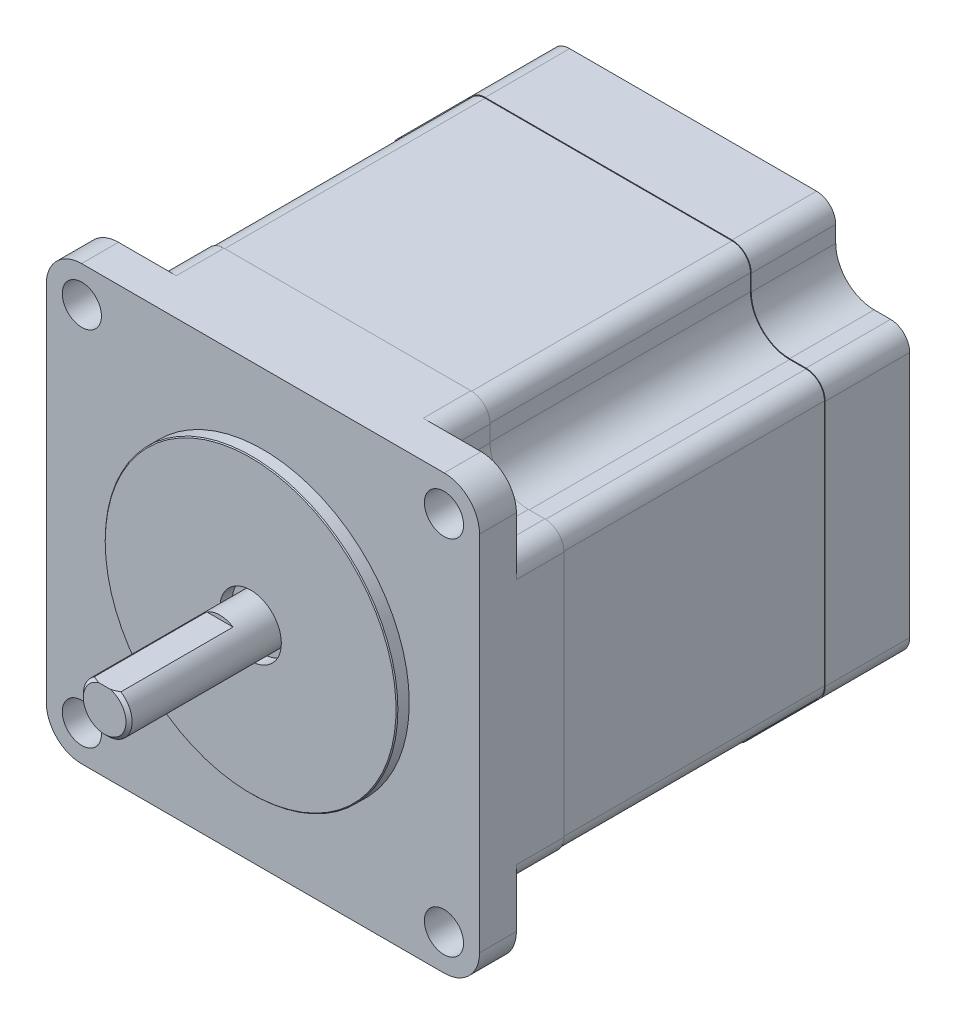
SolidWorks part; units mm, degrees
ref_plane "Front" through (0, 0, 0) normal (0, 0, 1) x (1, 0, 0)
ref_plane "Top" through (0, 0, 0) normal (0, 1, 0) x (1, 0, 0)
ref_plane "Right" through (0, 0, 0) normal (1, 0, 0) x (0, 0, -1)
sketch "Sketch1" plane through (0, 0, 0) normal (0, 0, 1) x (1, 0, 0)
  circle A0 centre (0, 0) radius 3.175
  dimension "D1" = 6.35
extrude "Boss-Extrude1" add sketch "Sketch1" along normal blind 20.6
sketch "Sketch2" plane through (0, 0, 0) normal (0, 0, -1) x (-1, 0, 0)
  circle A0 centre (0, 0) radius 19.05
  dimension "D1" = 38.1
extrude "Boss-Extrude2" add sketch "Sketch2" against normal blind 1.6
sketch "Sketch3" plane through (0, 0, 0) normal (0, 0, -1) x (-1, 0, 0)
  line L1 (23.6, -28.2) -> (-23.6, -28.2)
  line L2 (28.2, -23.6) -> (28.2, 23.6)
  line L3 (23.6, 28.2) -> (-23.6, 28.2)
  line L4 (-28.2, -23.6) -> (-28.2, 23.6)
  line L5 (28.2, -28.2) -> (-28.2, 28.2) construction
  line L6 (28.2, 28.2) -> (-28.2, -28.2) construction
  arc A0 (28.2, 23.6) -> (23.6, 28.2) centre (23.6, 23.6) ccw
  arc A1 (23.6, -28.2) -> (28.2, -23.6) centre (23.6, -23.6) ccw
  arc A2 (-23.6, -28.2) -> (-28.2, -23.6) centre (-23.6, -23.6) cw
  arc A3 (-23.6, 28.2) -> (-28.2, 23.6) centre (-23.6, 23.6) ccw
  point P0 (0, 0)
  dimension "D2" = 4.6
  dimension "D1" = 56.4
extrude "Boss-Extrude3" add sketch "Sketch3" along normal blind 4.8
sketch "Sketch4" plane through (0, 0, -4.8) normal (0, 0, -1) x (-1, 0, 0)
  line L0 (-12.9329, 0) -> (0, 0) construction
  line L1 (0, 0) -> (0, 12.5926) construction
  line L2 (-18.57, 23.57) -> (-18.57, 25.7)
  line L4 (28.2, 16.07) -> (28.2, -16.07)
  line L5 (-23.57, 18.57) -> (-25.7, 18.57)
  line L6 (16.07, 28.2) -> (-16.07, 28.2)
  line L7 (-28.2, 23.6) -> (-28.2, -23.6) construction
  line L8 (-28.2, 16.07) -> (-28.2, -16.07)
  line L9 (23.6, 28.2) -> (-23.6, 28.2) construction
  line L10 (23.57, 18.57) -> (25.7, 18.57)
  line L12 (18.57, 23.57) -> (18.57, 25.7)
  line L13 (18.57, -23.57) -> (18.57, -25.7)
  line L15 (23.57, -18.57) -> (25.7, -18.57)
  line L16 (16.07, -28.2) -> (-16.07, -28.2)
  line L17 (-23.57, -18.57) -> (-25.7, -18.57)
  line L19 (-18.57, -23.57) -> (-18.57, -25.7)
  arc A0 (-18.57, 25.7) -> (-16.07, 28.2) centre (-16.07, 25.7) cw
  arc A1 (-23.57, 18.57) -> (-18.57, 23.57) centre (-23.57, 23.57) ccw
  arc A2 (-25.7, 18.57) -> (-28.2, 16.07) centre (-25.7, 16.07) ccw
  arc A3 (25.7, 18.57) -> (28.2, 16.07) centre (25.7, 16.07) cw
  arc A4 (23.57, 18.57) -> (18.57, 23.57) centre (23.57, 23.57) cw
  arc A5 (18.57, 25.7) -> (16.07, 28.2) centre (16.07, 25.7) ccw
  arc A6 (18.57, -25.7) -> (16.07, -28.2) centre (16.07, -25.7) cw
  arc A7 (23.57, -18.57) -> (18.57, -23.57) centre (23.57, -23.57) ccw
  arc A8 (25.7, -18.57) -> (28.2, -16.07) centre (25.7, -16.07) ccw
  arc A9 (-25.7, -18.57) -> (-28.2, -16.07) centre (-25.7, -16.07) cw
  arc A10 (-23.57, -18.57) -> (-18.57, -23.57) centre (-23.57, -23.57) cw
  arc A11 (-18.57, -25.7) -> (-16.07, -28.2) centre (-16.07, -25.7) ccw
  point P16 (28.2, 0)
  point P27 (0, 28.2)
  point P49 (0, -28.2)
  point P51 (-28.2, 0)
  dimension "D2" = 47.14
  dimension "D3" = 2.5
  dimension "4.6*2" = 10
  dimension "D4" = 47.14
extrude "Boss-Extrude4" add sketch "Sketch4" along normal blind 51.2
sketch "Sketch7" plane through (0, 0, 20.6) normal (0, 0, 1) x (1, 0, 0)
  line L1 (-1.7103, 2.675) -> (1.7103, 2.675)
  line L2 (-1.7103, 2.675) -> (-1.7103, 3.7877)
  line L3 (-1.7103, 3.7877) -> (1.7103, 3.7877)
  line L4 (1.7103, 2.675) -> (1.7103, 3.7877)
  circle A0 centre (0, 0) radius 3.175 construction
  dimension "D1" = 5.85
extrude "Cut-Extrude5" cut sketch "Sketch7" against normal blind 15
sketch "Sketch8" plane through (0, 0, 0) normal (0, 0, 1) x (1, 0, 0)
  line L0 (-13.3219, 0) -> (0, 0) construction
  line L1 (0, 0) -> (0, 15.3153) construction
  circle A0 centre (-23.57, 23.57) radius 2.55
  circle A1 centre (23.57, 23.57) radius 2.55
  circle A2 centre (23.57, -23.57) radius 2.55
  circle A3 centre (-23.57, -23.57) radius 2.55
  dimension "D2" = 47.14
  dimension "D3" = 5.1
  dimension "D1" = 47.14
extrude "Cut-Extrude6" cut sketch "Sketch8" against normal up to next
ref_plane "Plane1" through (0, 0, -28) normal (0, 0, 1) x (1, 0, 0)
sketch "Sketch9" plane through (0, 0, -28) normal (0, 0, 1) x (1, 0, 0)
  line L24 (18.47, 23.57) -> (18.47, 25.7)
  line L25 (25.7, 18.47) -> (23.57, 18.47)
  line L26 (28.1, -16.07) -> (28.1, 16.07)
  line L27 (23.57, -18.47) -> (25.7, -18.47)
  line L28 (18.47, -25.7) -> (18.47, -23.57)
  line L29 (-16.07, -28.1) -> (16.07, -28.1)
  line L30 (-18.47, -23.57) -> (-18.47, -25.7)
  line L31 (-25.7, -18.47) -> (-23.57, -18.47)
  line L32 (-28.1, 16.07) -> (-28.1, -16.07)
  line L33 (-23.57, 18.47) -> (-25.7, 18.47)
  line L34 (-18.47, 25.7) -> (-18.47, 23.57)
  line L35 (16.07, 28.1) -> (-16.07, 28.1)
  line L36 (18.47, 23.57) -> (18.47, 25.7)
  line L37 (25.7, 18.47) -> (23.57, 18.47)
  line L38 (28.1, -16.07) -> (28.1, 16.07)
  line L39 (23.57, -18.47) -> (25.7, -18.47)
  line L40 (18.47, -25.7) -> (18.47, -23.57)
  line L41 (-16.07, -28.1) -> (16.07, -28.1)
  line L42 (-18.47, -23.57) -> (-18.47, -25.7)
  line L43 (-25.7, -18.47) -> (-23.57, -18.47)
  line L44 (-28.1, 16.07) -> (-28.1, -16.07)
  line L45 (-23.57, 18.47) -> (-25.7, 18.47)
  line L46 (-18.47, 25.7) -> (-18.47, 23.57)
  line L47 (16.07, 28.1) -> (-16.07, 28.1)
  line L48 (18.57, 23.57) -> (18.57, 25.7)
  line L49 (25.7, 18.57) -> (23.57, 18.57)
  line L50 (28.2, -16.07) -> (28.2, 16.07)
  line L51 (23.57, -18.57) -> (25.7, -18.57)
  line L52 (18.57, -25.7) -> (18.57, -23.57)
  line L53 (-16.07, -28.2) -> (16.07, -28.2)
  line L54 (-18.57, -23.57) -> (-18.57, -25.7)
  line L55 (-25.7, -18.57) -> (-23.57, -18.57)
  line L56 (-28.2, 16.07) -> (-28.2, -16.07)
  line L57 (-23.57, 18.57) -> (-25.7, 18.57)
  line L58 (-18.57, 25.7) -> (-18.57, 23.57)
  line L59 (16.07, 28.2) -> (-16.07, 28.2)
  line L60 (18.57, 23.57) -> (18.57, 25.7)
  line L61 (25.7, 18.57) -> (23.57, 18.57)
  line L62 (28.2, -16.07) -> (28.2, 16.07)
  line L63 (23.57, -18.57) -> (25.7, -18.57)
  line L64 (18.57, -25.7) -> (18.57, -23.57)
  line L65 (-16.07, -28.2) -> (16.07, -28.2)
  line L66 (-18.57, -23.57) -> (-18.57, -25.7)
  line L67 (-25.7, -18.57) -> (-23.57, -18.57)
  line L68 (-28.2, 16.07) -> (-28.2, -16.07)
  line L69 (-23.57, 18.57) -> (-25.7, 18.57)
  line L70 (-18.57, 25.7) -> (-18.57, 23.57)
  line L71 (16.07, 28.2) -> (-16.07, 28.2)
  arc A24 (18.47, 25.7) -> (16.07, 28.1) centre (16.07, 25.7) ccw
  arc A25 (18.47, 23.57) -> (23.57, 18.47) centre (23.57, 23.57) ccw
  arc A26 (28.1, 16.07) -> (25.7, 18.47) centre (25.7, 16.07) ccw
  arc A27 (25.7, -18.47) -> (28.1, -16.07) centre (25.7, -16.07) ccw
  arc A28 (23.57, -18.47) -> (18.47, -23.57) centre (23.57, -23.57) ccw
  arc A29 (16.07, -28.1) -> (18.47, -25.7) centre (16.07, -25.7) ccw
  arc A30 (-18.47, -25.7) -> (-16.07, -28.1) centre (-16.07, -25.7) ccw
  arc A31 (-18.47, -23.57) -> (-23.57, -18.47) centre (-23.57, -23.57) ccw
  arc A32 (-28.1, -16.07) -> (-25.7, -18.47) centre (-25.7, -16.07) ccw
  arc A33 (-25.7, 18.47) -> (-28.1, 16.07) centre (-25.7, 16.07) ccw
  arc A34 (-23.57, 18.47) -> (-18.47, 23.57) centre (-23.57, 23.57) ccw
  arc A35 (-16.07, 28.1) -> (-18.47, 25.7) centre (-16.07, 25.7) ccw
  arc A36 (18.47, 25.7) -> (16.07, 28.1) centre (16.07, 25.7) ccw
  arc A37 (18.47, 23.57) -> (23.57, 18.47) centre (23.57, 23.57) ccw
  arc A38 (28.1, 16.07) -> (25.7, 18.47) centre (25.7, 16.07) ccw
  arc A39 (25.7, -18.47) -> (28.1, -16.07) centre (25.7, -16.07) ccw
  arc A40 (23.57, -18.47) -> (18.47, -23.57) centre (23.57, -23.57) ccw
  arc A41 (16.07, -28.1) -> (18.47, -25.7) centre (16.07, -25.7) ccw
  arc A42 (-18.47, -25.7) -> (-16.07, -28.1) centre (-16.07, -25.7) ccw
  arc A43 (-18.47, -23.57) -> (-23.57, -18.47) centre (-23.57, -23.57) ccw
  arc A44 (-28.1, -16.07) -> (-25.7, -18.47) centre (-25.7, -16.07) ccw
  arc A45 (-25.7, 18.47) -> (-28.1, 16.07) centre (-25.7, 16.07) ccw
  arc A46 (-23.57, 18.47) -> (-18.47, 23.57) centre (-23.57, 23.57) ccw
  arc A47 (-16.07, 28.1) -> (-18.47, 25.7) centre (-16.07, 25.7) ccw
  arc A48 (18.57, 25.7) -> (16.07, 28.2) centre (16.07, 25.7) ccw
  arc A49 (18.57, 23.57) -> (23.57, 18.57) centre (23.57, 23.57) ccw
  arc A50 (28.2, 16.07) -> (25.7, 18.57) centre (25.7, 16.07) ccw
  arc A51 (25.7, -18.57) -> (28.2, -16.07) centre (25.7, -16.07) ccw
  arc A52 (23.57, -18.57) -> (18.57, -23.57) centre (23.57, -23.57) ccw
  arc A53 (16.07, -28.2) -> (18.57, -25.7) centre (16.07, -25.7) ccw
  arc A54 (-18.57, -25.7) -> (-16.07, -28.2) centre (-16.07, -25.7) ccw
  arc A55 (-18.57, -23.57) -> (-23.57, -18.57) centre (-23.57, -23.57) ccw
  arc A56 (-28.2, -16.07) -> (-25.7, -18.57) centre (-25.7, -16.07) ccw
  arc A57 (-25.7, 18.57) -> (-28.2, 16.07) centre (-25.7, 16.07) ccw
  arc A58 (-23.57, 18.57) -> (-18.57, 23.57) centre (-23.57, 23.57) ccw
  arc A59 (-16.07, 28.2) -> (-18.57, 25.7) centre (-16.07, 25.7) ccw
  arc A60 (18.57, 25.7) -> (16.07, 28.2) centre (16.07, 25.7) ccw
  arc A61 (18.57, 23.57) -> (23.57, 18.57) centre (23.57, 23.57) ccw
  arc A62 (28.2, 16.07) -> (25.7, 18.57) centre (25.7, 16.07) ccw
  arc A63 (25.7, -18.57) -> (28.2, -16.07) centre (25.7, -16.07) ccw
  arc A64 (23.57, -18.57) -> (18.57, -23.57) centre (23.57, -23.57) ccw
  arc A65 (16.07, -28.2) -> (18.57, -25.7) centre (16.07, -25.7) ccw
  arc A66 (-18.57, -25.7) -> (-16.07, -28.2) centre (-16.07, -25.7) ccw
  arc A67 (-18.57, -23.57) -> (-23.57, -18.57) centre (-23.57, -23.57) ccw
  arc A68 (-28.2, -16.07) -> (-25.7, -18.57) centre (-25.7, -16.07) ccw
  arc A69 (-25.7, 18.57) -> (-28.2, 16.07) centre (-25.7, 16.07) ccw
  arc A70 (-23.57, 18.57) -> (-18.57, 23.57) centre (-23.57, 23.57) ccw
  arc A71 (-16.07, 28.2) -> (-18.57, 25.7) centre (-16.07, 25.7) ccw
  dimension "D1" = 0.1
  dimension "D2" = 0
extrude "Cut-Extrude7" cut sketch "Sketch9" against normal mid plane 34
chamfer "Chamfer1" distance 0.12 angle 45 1 edges at (-19.05, 0, 1.6)
chamfer "Chamfer2" distance 0.4 angle 45 1 edges at (0, -3.175, 20.6)
sketch "Sketch10" plane through (0, 0, -56) normal (0, 0, -1) x (-1, 0, 0)
  circle A0 centre (0, 0) radius 5.5
  dimension "D1" = 11
extrude "Cut-Extrude8" cut sketch "Sketch10" against normal blind 5
sketch "Sketch11" plane through (0, 0, -51) normal (0, 0, -1) x (-1, 0, 0)
  circle A0 centre (0, 0) radius 3.175
  arc A1 (-1.7103, 2.675) -> (1.7103, 2.675) centre (0, 0) ccw construction
extrude "Boss-Extrude5" add sketch "Sketch11" along normal blind 2.5
chamfer "Chamfer3" distance 0.4 angle 45 1 edges at (-3.175, 0, -53.5)
chamfer "Chamfer4" distance 0.4 angle 45 1 edges at (-5.5, 0, -56)
sketch "Sketch12" plane through (0, 0, 1.6) normal (0, 0, 1) x (1, 0, 0)
  circle A0 centre (0, 0) radius 4
  circle A1 centre (0, 0) radius 3.175 construction
  circle A2 centre (0, 0) radius 3.175
  dimension "D1" = 8
extrude "Cut-Extrude9" cut sketch "Sketch12" against normal up to surface (1.6 mm away) up to face at (-26.12, -23.57, 0)
